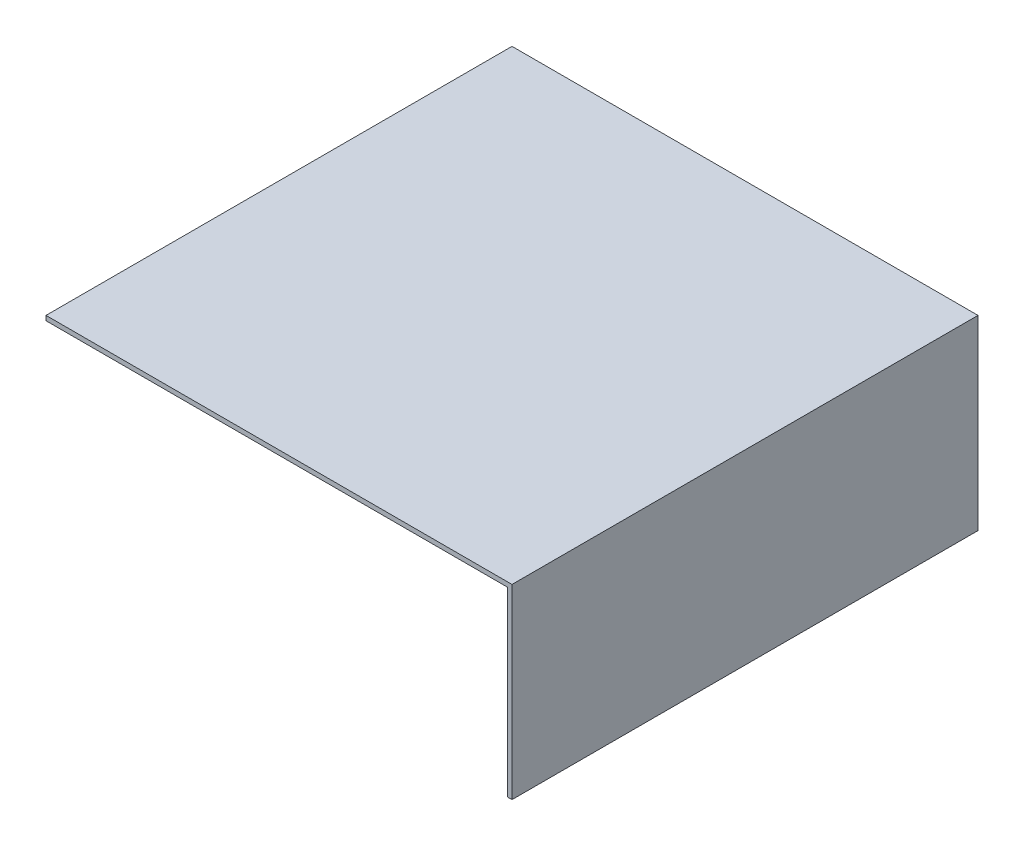
SolidWorks part; units mm, degrees
ref_plane "Front Plane" through (0, 0, 0) normal (0, 0, 1) x (1, 0, 0)
ref_plane "Top Plane" through (0, 0, 0) normal (0, 1, 0) x (1, 0, 0)
ref_plane "Right Plane" through (0, 0, 0) normal (1, 0, 0) x (0, 0, -1)
sketch "Sketch1" plane through (0, 0, 0) normal (0, 0, 1) x (1, 0, 0)
  line L0 (-500, 0) -> (0, 0)
  line L1 (0, 0) -> (0, -200)
  line L2 (0, -200) -> (-5, -200)
  line L3 (-5, -200) -> (-5, -5)
  line L4 (-5, -5) -> (-500, -5)
  line L5 (-500, -5) -> (-500, 0)
  point P4 (-3.2056, -3.546)
  point P8 (-22.3055, -0.4665)
  dimension "D1" = 200
  dimension "D2" = 5
  dimension "D3" = 500
extrude "Boss-Extrude1" add sketch "Sketch1" along normal mid plane 500
